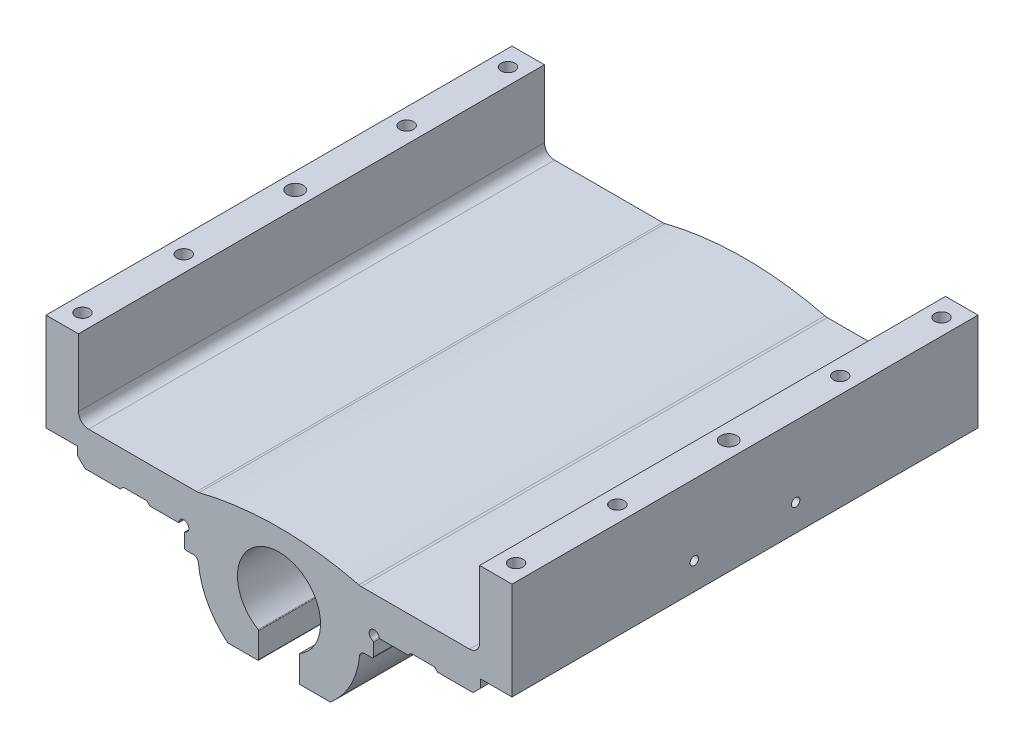
SolidWorks part; units mm, degrees
ref_plane "前视基准面" through (0, 0, 0) normal (0, 0, 1) x (1, 0, 0)
ref_plane "上视基准面" through (0, 0, 0) normal (0, 1, 0) x (1, 0, 0)
ref_plane "右视基准面" through (0, 0, 0) normal (1, 0, 0) x (0, 0, -1)
sketch "草图1" plane through (0, 0, 0) normal (0, 0, 1) x (1, 0, 0)
  line L160 (-40.6202, 87.2009) -> (-94, 87.2009)
  line L161 (-99, 92.2009) -> (-99, 134.4938)
  line L162 (-99.1464, 134.8474) -> (-100.8536, 136.5545)
  line L163 (-101.2071, 136.7009) -> (-112.7929, 136.7009)
  line L164 (-113.1464, 136.5545) -> (-114.8536, 134.8474)
  line L165 (-115, 134.4938) -> (-115, 76.408)
  line L166 (-114.8536, 76.0545) -> (-114.1464, 75.3474)
  line L167 (-113.7929, 75.2009) -> (-103.5711, 75.2009)
  line L168 (-100.0355, 73.7364) -> (-94.75, 68.4509)
  line L169 (-94.75, 68.4509) -> (-79.3, 68.4509)
  line L170 (-79.3, 68.4509) -> (-76.8, 70.9509)
  line L171 (-76.8, 70.9509) -> (-65.2, 70.9509)
  line L172 (-65.2, 70.9509) -> (-62.7, 68.4509)
  line L173 (-62.7, 68.4509) -> (-50, 68.4509)
  line L174 (-49.5, 68.9509) -> (-49.5, 69.4509)
  line L175 (-46.75, 66.5462) -> (-46.75, 60.4509)
  line L176 (-45.75, 59.4509) -> (-42.287, 59.4509)
  line L177 (-25.0998, 30.2009) -> (-10.5, 30.2009)
  line L178 (-10, 30.7009) -> (-10, 43.0144)
  line L179 (10, 43.0144) -> (10, 30.7009)
  line L180 (10.5, 30.2009) -> (25.0998, 30.2009)
  line L181 (42.287, 59.4509) -> (45.75, 59.4509)
  line L182 (46.75, 60.4509) -> (46.75, 66.5462)
  line L183 (49.5, 69.4509) -> (49.5, 68.9509)
  line L184 (50, 68.4509) -> (62.7, 68.4509)
  line L185 (62.7, 68.4509) -> (65.2, 70.9509)
  line L186 (65.2, 70.9509) -> (76.8, 70.9509)
  line L187 (76.8, 70.9509) -> (79.3, 68.4509)
  line L188 (79.3, 68.4509) -> (94.75, 68.4509)
  line L189 (94.75, 68.4509) -> (100.0355, 73.7364)
  line L190 (103.5711, 75.2009) -> (113.7929, 75.2009)
  line L191 (114.1464, 75.3474) -> (114.8536, 76.0545)
  line L192 (115, 76.408) -> (115, 134.4938)
  line L193 (114.8536, 134.8474) -> (113.1464, 136.5545)
  line L194 (112.7929, 136.7009) -> (101.2071, 136.7009)
  line L195 (100.8536, 136.5545) -> (99.1464, 134.8474)
  line L196 (99, 134.4938) -> (99, 92.2009)
  line L197 (94, 87.2009) -> (40.6202, 87.2009)
  arc A186 (0, 92.2009) -> (-39.4076, 87.3502) centre (0, -70.2991) ccw
  arc A187 (-40.5, 87.2023) -> (-39.4076, 87.3502) centre (-40.6202, 92.2009) ccw
  arc A188 (-40.6202, 87.2009) -> (-40.5, 87.2023) centre (-40.6202, 92.2009) ccw
  arc A189 (-99, 92.2009) -> (-94, 87.2009) centre (-94, 92.2009) ccw
  arc A190 (-99, 134.4938) -> (-99.1464, 134.8474) centre (-99.5, 134.4938) ccw
  arc A191 (-100.8536, 136.5545) -> (-101.2071, 136.7009) centre (-101.2071, 136.2009) ccw
  arc A192 (-112.7929, 136.7009) -> (-113.1464, 136.5545) centre (-112.7929, 136.2009) ccw
  arc A193 (-114.8536, 134.8474) -> (-115, 134.4938) centre (-114.5, 134.4938) ccw
  arc A194 (-115, 76.408) -> (-114.8536, 76.0545) centre (-114.5, 76.408) ccw
  arc A195 (-114.1464, 75.3474) -> (-113.7929, 75.2009) centre (-113.7929, 75.7009) ccw
  arc A196 (-100.0355, 73.7364) -> (-103.5711, 75.2009) centre (-103.5711, 70.2009) ccw
  arc A197 (-50, 68.4509) -> (-49.5, 68.9509) centre (-50, 68.9509) ccw
  arc A198 (-46.375, 67.0303) -> (-49.5, 69.4509) centre (-47, 69.4509) ccw
  arc A199 (-46.375, 67.0303) -> (-46.75, 66.5462) centre (-46.25, 66.5462) ccw
  arc A200 (-46.75, 60.4509) -> (-45.75, 59.4509) centre (-45.75, 60.4509) ccw
  arc A201 (-39.7995, 57.2009) -> (-42.287, 59.4509) centre (-42.287, 56.9509) ccw
  arc A202 (-39.7995, 57.2009) -> (-25.4175, 30.3148) centre (0, 61.2009) ccw
  arc A203 (-25.4175, 30.3148) -> (-25.0998, 30.2009) centre (-25.0998, 30.7009) ccw
  arc A204 (-10.5, 30.2009) -> (-10, 30.7009) centre (-10.5, 30.7009) ccw
  arc A205 (-10, 43.0144) -> (-10.25, 43.4474) centre (-10.5, 43.0144) ccw
  arc A206 (10.25, 43.4474) -> (-10.25, 43.4474) centre (0, 61.2009) ccw
  arc A207 (10.25, 43.4474) -> (10, 43.0144) centre (10.5, 43.0144) ccw
  arc A208 (10, 30.7009) -> (10.5, 30.2009) centre (10.5, 30.7009) ccw
  arc A209 (25.0998, 30.2009) -> (25.4175, 30.3148) centre (25.0998, 30.7009) ccw
  arc A210 (25.4175, 30.3148) -> (39.7995, 57.2009) centre (0, 61.2009) ccw
  arc A211 (42.287, 59.4509) -> (39.7995, 57.2009) centre (42.287, 56.9509) ccw
  arc A212 (45.75, 59.4509) -> (46.75, 60.4509) centre (45.75, 60.4509) ccw
  arc A213 (46.75, 66.5462) -> (46.375, 67.0303) centre (46.25, 66.5462) ccw
  arc A214 (49.5, 69.4509) -> (46.375, 67.0303) centre (47, 69.4509) ccw
  arc A215 (49.5, 68.9509) -> (50, 68.4509) centre (50, 68.9509) ccw
  arc A216 (103.5711, 75.2009) -> (100.0355, 73.7364) centre (103.5711, 70.2009) ccw
  arc A217 (113.7929, 75.2009) -> (114.1464, 75.3474) centre (113.7929, 75.7009) ccw
  arc A218 (114.8536, 76.0545) -> (115, 76.408) centre (114.5, 76.408) ccw
  arc A219 (115, 134.4938) -> (114.8536, 134.8474) centre (114.5, 134.4938) ccw
  arc A220 (113.1464, 136.5545) -> (112.7929, 136.7009) centre (112.7929, 136.2009) ccw
  arc A221 (101.2071, 136.7009) -> (100.8536, 136.5545) centre (101.2071, 136.2009) ccw
  arc A222 (99.1464, 134.8474) -> (99, 134.4938) centre (99.5, 134.4938) ccw
  arc A223 (94, 87.2009) -> (99, 92.2009) centre (94, 92.2009) ccw
  arc A224 (40.5, 87.2023) -> (40.6202, 87.2009) centre (40.6202, 92.2009) ccw
  arc A225 (39.4076, 87.3502) -> (40.5, 87.2023) centre (40.6202, 92.2009) ccw
  arc A226 (39.4076, 87.3502) -> (0, 92.2009) centre (0, -70.2991) ccw
  dimension "D2" = 230
extrude "凸台-拉伸1" add sketch "草图1" along normal mid plane 230
sketch "草图2" plane through (0, 0, 115) normal (0, 0, 1) x (1, 0, 0)
  line L0 (0, 61.2009) -> (0, 99.6905) construction
  line L1 (-115, 69.4509) -> (-49, 69.4509)
  line L2 (-115, 69.4509) -> (-115, 64.4509)
  line L3 (-115, 64.4509) -> (-49, 64.4509)
  line L4 (-49, 69.4509) -> (-49, 64.4509)
  line L5 (-115, 136.7009) -> (115, 136.7009)
  line L6 (-115, 136.7009) -> (-115, 125.4509)
  line L7 (-115, 125.4509) -> (115, 125.4509)
  line L8 (115, 136.7009) -> (115, 125.4509)
  line L9 (-115, 134.4938) -> (-115, 76.408) construction
  line L11 (-94.75, 68.4509) -> (-79.3, 68.4509) construction
  line L12 (49, 69.4509) -> (49, 64.4509)
  line L13 (115, 64.4509) -> (49, 64.4509)
  line L14 (115, 69.4509) -> (115, 64.4509)
  line L15 (115, 69.4509) -> (49, 69.4509)
  line L16 (115, 76.408) -> (115, 134.4938) construction
  line L17 (112.7929, 136.7009) -> (101.2071, 136.7009) construction
  line L18 (-113.7929, 75.2009) -> (-103.5711, 75.2009) construction
  line L19 (-115, 77.2009) -> (-99.5, 77.2009)
  line L20 (-115, 77.2009) -> (-115, 73.2009)
  line L21 (-115, 73.2009) -> (-99.5, 73.2009)
  line L22 (-99.5, 77.2009) -> (-99.5, 73.2009)
  line L23 (99.5, 77.2009) -> (99.5, 73.2009)
  line L24 (115, 73.2009) -> (99.5, 73.2009)
  line L25 (115, 77.2009) -> (115, 73.2009)
  line L26 (115, 77.2009) -> (99.5, 77.2009)
  line L27 (-100.0355, 73.7364) -> (-94.75, 68.4509) construction
  dimension "D1" = 5
  dimension "D2" = 1
  dimension "D3" = 98
  dimension "D4" = 11.25
  dimension "D5" = 2
  dimension "D7" = 15.5
extrude "切除-拉伸1" cut sketch "草图2" against normal through all
hole_wizard "M8 螺纹孔1" positions "草图6" profile "草图5" tap size "M8" standard "ISO"
sketch "草图6" plane through (0, 125.4509, 0) normal (0, 1, 0) x (1, 0, 0)
  line L0 (0, -115) -> (0, 0) construction
  line L1 (-39.4076, -115) -> (39.4076, -115) construction
  line L2 (0, 0) -> (-115, 0) construction
  line L3 (-115, 115) -> (-115, -115) construction
  point P0 (-107, 105)
  point P2 (-107, -55)
  point P4 (-107, 55)
  point P6 (-107, -105)
  point P8 (107, 55)
  point P10 (107, -105)
  point P12 (107, 105)
  point P14 (107, -55)
  dimension "D1" = 210
  dimension "D2" = 110
  dimension "D3" = 214
sketch "草图5" plane through (-107, 125.4509, -105) normal (1, 0, 0) x (0, 0, 1)
  line L0 (0, 0) -> (0, 27.0429)
  line L1 (0, 27.0429) -> (3.4, 25)
  line L2 (3.4, 25) -> (3.4, 0)
  line L5 (3.4, 0) -> (0, 0)
  line L10 (0, 27.0429) -> (-3.4, 25) construction
  line L11 (0, -6.35) -> (0, 107.95) construction
  dimension "螺纹孔钻头直径" = 6.8
  dimension "螺纹孔钻头深度" = 25
  dimension "导头角度" = 118
cosmetic thread "孔螺蚊线1" parameters "D1"=25, "D2"=8
cosmetic thread "孔螺蚊线2" parameters "D1"=25, "D2"=8
cosmetic thread "孔螺蚊线3" parameters "D1"=25, "D2"=8
cosmetic thread "孔螺蚊线4" parameters "D1"=25, "D2"=8
cosmetic thread "孔螺蚊线5" parameters "D1"=25, "D2"=8
cosmetic thread "孔螺蚊线6" parameters "D1"=25, "D2"=8
cosmetic thread "孔螺蚊线7" parameters "D1"=25, "D2"=8
cosmetic thread "孔螺蚊线8" parameters "D1"=25, "D2"=8
hole_wizard "大小mm 暗销孔1" positions "草图8" profile "草图7" hole size "Ø8.0" standard "ISO"
sketch "草图8" plane through (0, 125.4509, 0) normal (0, 1, 0) x (1, 0, 0)
  line L0 (-107, 55) -> (-107, -55) construction
  line L1 (-107, -55) -> (107, -55) construction
  line L2 (107, -55) -> (107, 55) construction
  point P0 (-107, 0)
  point P2 (107, 0)
sketch "草图7" plane through (-107, 125.4509, 0) normal (1, 0, 0) x (0, 0, 1)
  line L0 (0, 0) -> (0, 17.4034)
  line L1 (0, 17.4034) -> (4, 15)
  line L2 (4, 15) -> (4, 0)
  line L5 (4, 0) -> (0, 0)
  line L10 (0, 17.4034) -> (-4, 15) construction
  line L11 (0, -6.35) -> (0, 107.95) construction
  dimension "孔直径" = 8
  dimension "孔深度" = 15
  dimension "导头角度" = 118
hole_wizard "M5 螺纹孔1" positions "草图14" profile "草图13" tap size "M5" standard "ISO"
sketch "草图14" plane through (115, 0, 0) normal (1, 0, 0) x (0, 0, -1)
  line L0 (0, 124.4651) -> (0, 98.4915) construction
  line L2 (115, 125.4509) -> (-115, 125.4509) construction
  point P0 (-25, 90.4509)
  point P2 (25, 90.4509)
  dimension "D1" = 50
  dimension "D2" = 35
sketch "草图13" plane through (115, 90.4509, 25) normal (0, 1, 0) x (0, 0, -1)
  line L0 (0, 0) -> (0, 13.6618)
  line L1 (0, 13.6618) -> (2.1, 12.4)
  line L2 (2.1, 12.4) -> (2.1, 0)
  line L5 (2.1, 0) -> (0, 0)
  line L10 (0, 13.6618) -> (-2.1, 12.4) construction
  line L11 (0, -6.35) -> (0, 107.95) construction
  dimension "螺纹孔钻头直径" = 4.2
  dimension "螺纹孔钻头深度" = 12.4
  dimension "导头角度" = 118
cosmetic thread "孔螺蚊线15" parameters "D1"=10, "D2"=5
cosmetic thread "孔螺蚊线16" parameters "D1"=10, "D2"=5
mirror "镜向1" about plane through (0, 0, 0) normal (1, 0, 0) of "M5 螺纹孔1"
